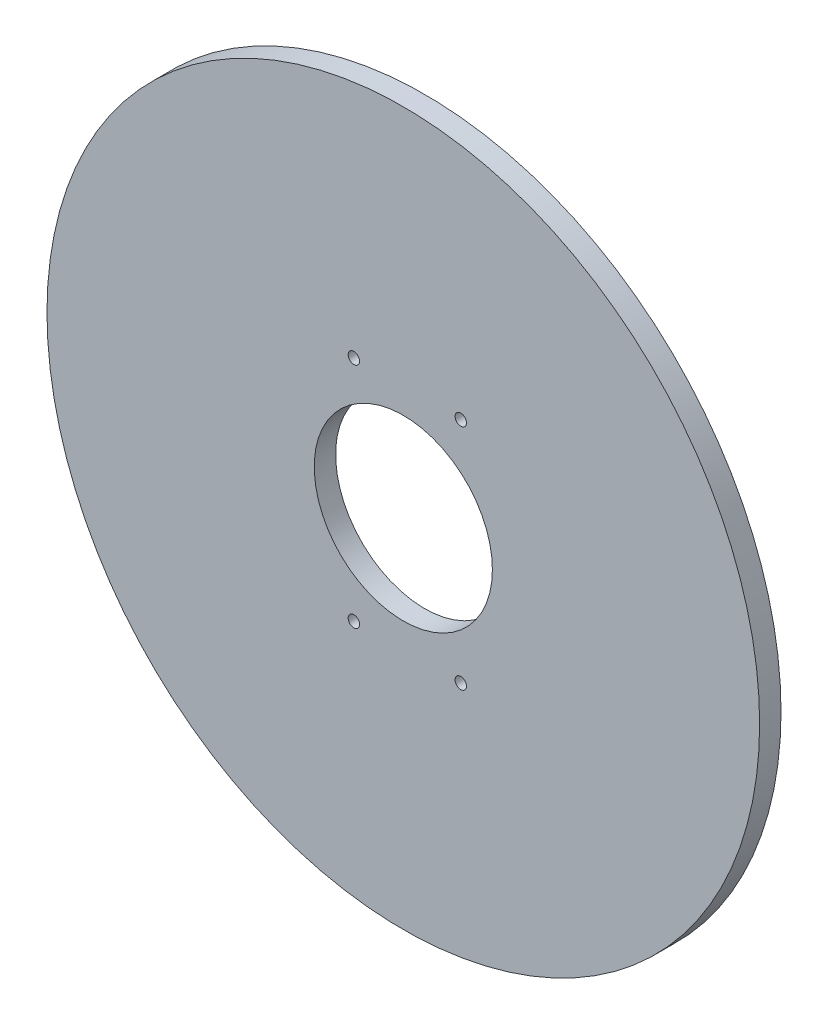
SolidWorks part; units mm, degrees
material "Teak"
ref_plane "Front Plane" through (0, 0, 0) normal (0, 0, 1) x (1, 0, 0)
ref_plane "Top Plane" through (0, 0, 0) normal (0, 1, 0) x (1, 0, 0)
ref_plane "Right Plane" through (0, 0, 0) normal (1, 0, 0) x (0, 0, -1)
sketch "Sketch1" plane through (0, 0, 0) normal (0, 0, 1) x (1, 0, 0)
  circle A0 centre (0, 0) radius 100
  circle A1 centre (0, 0) radius 25
  dimension "D1" = 200
  dimension "D2" = 50
extrude "Boss-Extrude1" add sketch "Sketch1" along normal blind 6
sketch "Sketch2" plane through (0, 0, 0) normal (0, 0, -1) x (-1, 0, 0)
  line L0 (25, 0) -> (-25, 0) construction
  circle A0 centre (-16.1297, 32) radius 1.6
  circle A1 centre (13.8703, 32) radius 1.6
  circle A2 centre (0, 0) radius 25 construction
  circle A3 centre (13.8703, -32) radius 1.6
  circle A4 centre (-16.1297, -32) radius 1.6
  dimension "D1" = 3.2
  dimension "D2" = 3.2
extrude "Cut-Extrude1" cut sketch "Sketch2" against normal through all
